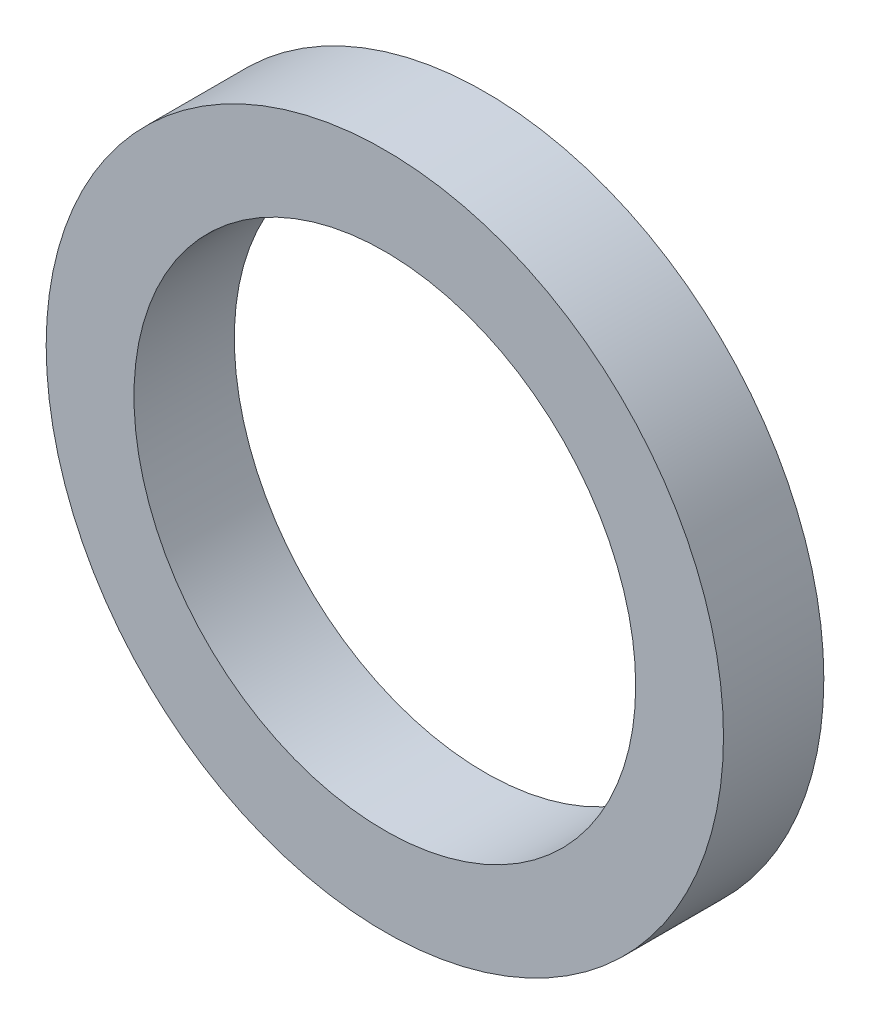
SolidWorks part; units mm, degrees
ref_plane "前视基准面" through (0, 0, 0) normal (0, 0, 1) x (1, 0, 0)
ref_plane "上视基准面" through (0, 0, 0) normal (0, 1, 0) x (1, 0, 0)
ref_plane "右视基准面" through (0, 0, 0) normal (1, 0, 0) x (0, 0, -1)
sketch "草图1" plane through (0, 0, 0) normal (0, 0, 1) x (1, 0, 0)
  circle A0 centre (0, 0) radius 10
  circle A1 centre (0, 0) radius 13.5
  dimension "D1" = 20
  dimension "D2" = 27
extrude "凸台-拉伸1" add sketch "草图1" along normal blind 4 contours A1
